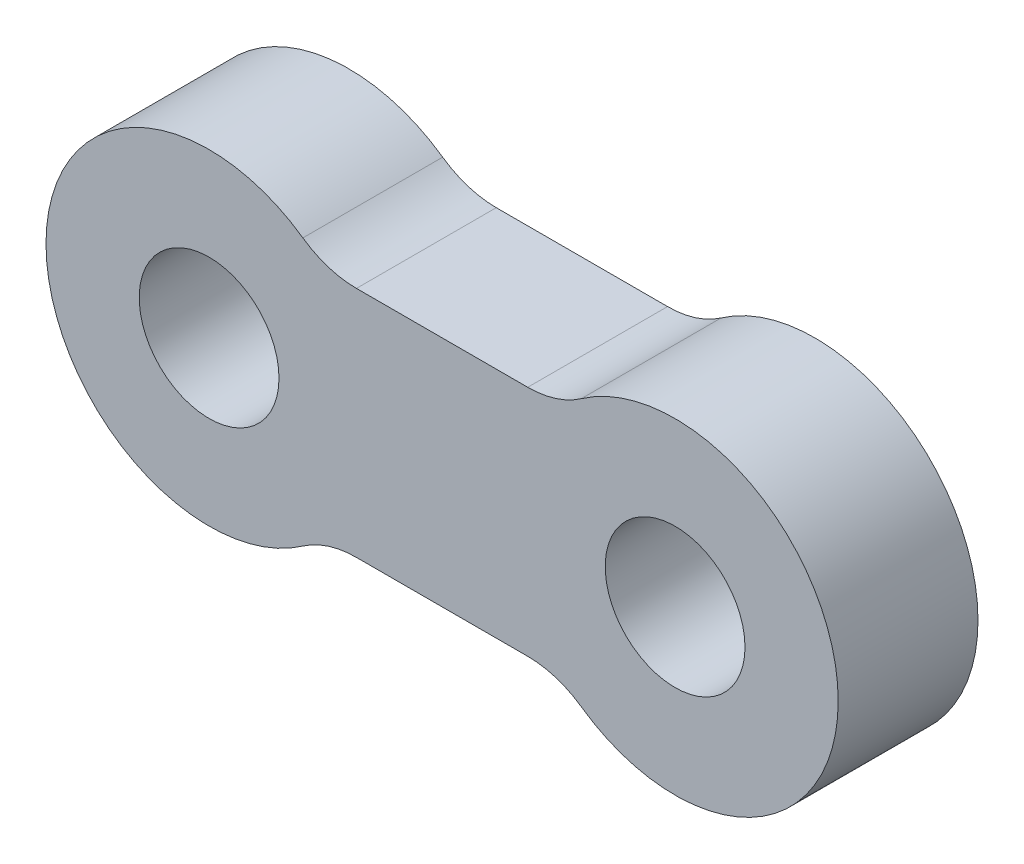
SolidWorks part; units mm, degrees
ref_plane "前视基准面" through (0, 0, 0) normal (0, 0, 1) x (1, 0, 0)
ref_plane "上视基准面" through (0, 0, 0) normal (0, 1, 0) x (1, 0, 0)
ref_plane "右视基准面" through (0, 0, 0) normal (1, 0, 0) x (0, 0, -1)
sketch "草图1" plane through (0, 0, 0) normal (0, 0, 1) x (1, 0, 0)
  line L0 (0, 0) -> (10, 0) construction
  line L1 (0, 3.5) -> (10, 3.5)
  line L2 (0, -3.5) -> (10, -3.5)
  arc A0 (0, 3.5) -> (0, -3.5) centre (0, 0) ccw
  arc A1 (10, -3.5) -> (10, 3.5) centre (10, 0) ccw
  circle A2 centre (0, 0) radius 1.5
  circle A3 centre (10, 0) radius 1.5
  point P3 (5, 0)
  dimension "D1" = 3
  dimension "D3" = 10
  dimension "D2" = 7
extrude "凸台-拉伸1" add sketch "草图1" along normal blind 3
sketch "草图2" plane through (0, 0, 3) normal (0, 0, 1) x (1, 0, 0)
  line L0 (3.1623, 2.5) -> (6.8377, 2.5)
  line L1 (5, 5.5809) -> (5, -6.2235) construction
  line L2 (-5.4918, 0) -> (22.4534, 0) construction
  line L3 (0, 3.5) -> (10, 3.5)
  line L4 (10, 3.5) -> (0, 3.5) construction
  line L5 (3.1623, -2.5) -> (6.8377, -2.5)
  line L6 (0, -3.5) -> (10, -3.5)
  arc A0 (0, 3.5) -> (2.0124, 2.8636) centre (0, 0) cw
  arc A1 (0, 3.5) -> (0, -3.5) centre (0, 0) ccw construction
  arc A2 (10, 3.5) -> (7.9876, 2.8636) centre (10, 0) ccw
  circle A3 centre (10, 0) radius 1.5 construction
  circle A4 centre (0, 0) radius 1.5 construction
  arc A5 (7.9876, 2.8636) -> (6.8377, 2.5) centre (6.8377, 4.5) cw
  arc A6 (3.1623, 2.5) -> (2.0124, 2.8636) centre (3.1623, 4.5) cw
  arc A7 (0, -3.5) -> (2.0124, -2.8636) centre (0, 0) ccw
  arc A8 (3.1623, -2.5) -> (2.0124, -2.8636) centre (3.1623, -4.5) ccw
  arc A9 (7.9876, -2.8636) -> (6.8377, -2.5) centre (6.8377, -4.5) ccw
  arc A10 (10, -3.5) -> (7.9876, -2.8636) centre (10, 0) cw
  point P24 (7.5505, 2.5)
  point P27 (2.4495, 2.5)
  dimension "D1" = 5
  dimension "D2" = 2
extrude "切除-拉伸1" cut sketch "草图2" against normal through all
